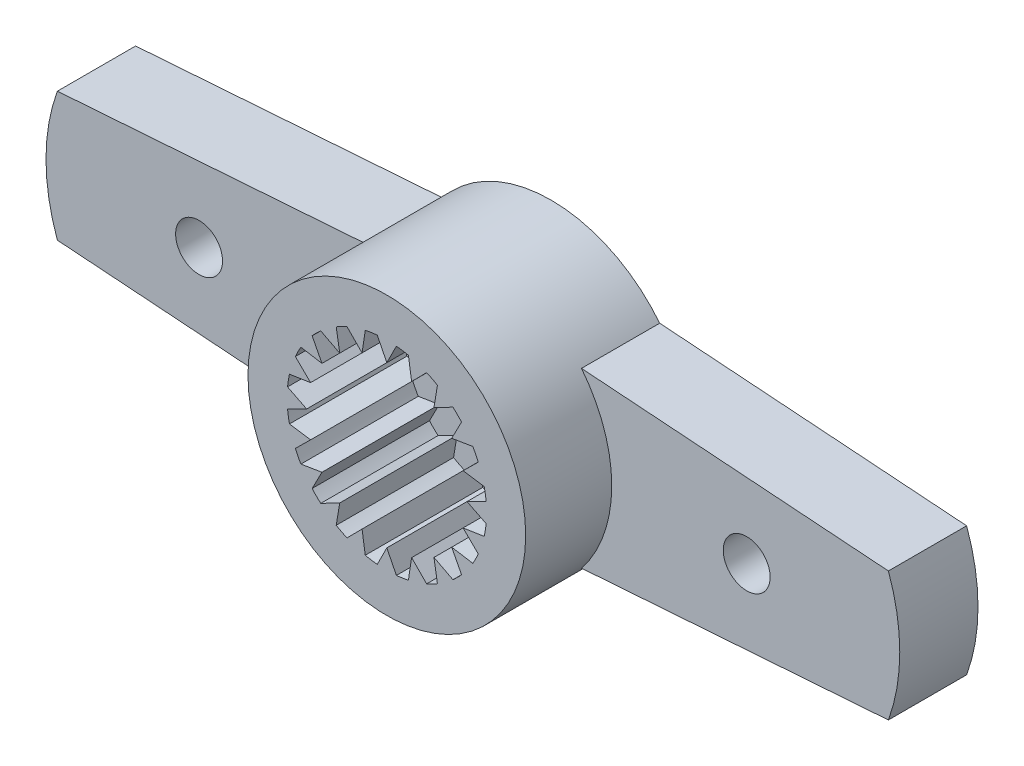
SolidWorks part; units mm, degrees
ref_plane "Front Plane" through (0, 0, 0) normal (0, 0, 1) x (1, 0, 0)
ref_plane "Top Plane" through (0, 0, 0) normal (0, 1, 0) x (1, 0, 0)
ref_plane "Right Plane" through (0, 0, 0) normal (1, 0, 0) x (0, 0, -1)
sketch "Sketch2" plane through (0, 0, 0) normal (0, 0, 1) x (1, 0, 0)
  circle A0 centre (0, 0) radius 3.55
  dimension "D1" = 7.1
sketch "Sketch3" plane through (0, 0, 0) normal (0, 0, 1) x (1, 0, 0)
  line L0 (-0.2447, 2.5382) -> (0, 2.05)
  line L1 (0, 2.05) -> (0.2447, 2.5382)
  line L2 (0.5516, 2.4896) -> (0.6335, 1.9497)
  line L3 (0.6335, 1.9497) -> (1.0171, 2.3384)
  line L4 (1.294, 2.1973) -> (1.205, 1.6585)
  line L5 (1.205, 1.6585) -> (1.6899, 1.9096)
  line L6 (1.9096, 1.6899) -> (1.6585, 1.205)
  line L7 (1.6585, 1.205) -> (2.1973, 1.294)
  line L8 (2.3384, 1.0171) -> (1.9497, 0.6335)
  line L9 (1.9497, 0.6335) -> (2.4896, 0.5516)
  line L10 (2.5382, 0.2447) -> (2.05, 0)
  line L11 (2.05, 0) -> (2.5382, -0.2447)
  line L12 (2.4896, -0.5516) -> (1.9497, -0.6335)
  line L13 (1.9497, -0.6335) -> (2.3384, -1.0171)
  line L14 (2.1973, -1.294) -> (1.6585, -1.205)
  line L15 (1.6585, -1.205) -> (1.9096, -1.6899)
  line L16 (1.6899, -1.9096) -> (1.205, -1.6585)
  line L17 (1.205, -1.6585) -> (1.294, -2.1973)
  line L18 (1.0171, -2.3384) -> (0.6335, -1.9497)
  line L19 (0.6335, -1.9497) -> (0.5516, -2.4896)
  line L20 (0.2447, -2.5382) -> (0, -2.05)
  line L21 (0, -2.05) -> (-0.2447, -2.5382)
  line L22 (-0.5516, -2.4896) -> (-0.6335, -1.9497)
  line L23 (-0.6335, -1.9497) -> (-1.0171, -2.3384)
  line L24 (-1.294, -2.1973) -> (-1.205, -1.6585)
  line L25 (-1.205, -1.6585) -> (-1.6899, -1.9096)
  line L26 (-1.9096, -1.6899) -> (-1.6585, -1.205)
  line L27 (-1.6585, -1.205) -> (-2.1973, -1.294)
  line L28 (-2.3384, -1.0171) -> (-1.9497, -0.6335)
  line L29 (-1.9497, -0.6335) -> (-2.4896, -0.5516)
  line L30 (-2.5382, -0.2447) -> (-2.05, 0)
  line L31 (-2.05, 0) -> (-2.5382, 0.2447)
  line L32 (-2.4896, 0.5516) -> (-1.9497, 0.6335)
  line L33 (-1.9497, 0.6335) -> (-2.3384, 1.0171)
  line L34 (-2.1973, 1.294) -> (-1.6585, 1.205)
  line L35 (-1.6585, 1.205) -> (-1.9096, 1.6899)
  line L36 (-1.6899, 1.9096) -> (-1.205, 1.6585)
  line L37 (-1.205, 1.6585) -> (-1.294, 2.1973)
  line L38 (-1.0171, 2.3384) -> (-0.6335, 1.9497)
  line L39 (-0.6335, 1.9497) -> (-0.5516, 2.4896)
  arc A0 (-0.2447, 2.5382) -> (0.2447, 2.5382) centre (0, 0) cw
  arc A2 (0.5516, 2.4896) -> (1.0171, 2.3384) centre (0, 0) cw
  arc A3 (1.294, 2.1973) -> (1.6899, 1.9096) centre (0, 0) cw
  arc A4 (1.9096, 1.6899) -> (2.1973, 1.294) centre (0, 0) cw
  arc A5 (2.3384, 1.0171) -> (2.4896, 0.5516) centre (0, 0) cw
  arc A6 (2.5382, 0.2447) -> (2.5382, -0.2447) centre (0, 0) cw
  arc A7 (2.4896, -0.5516) -> (2.3384, -1.0171) centre (0, 0) cw
  arc A8 (2.1973, -1.294) -> (1.9096, -1.6899) centre (0, 0) cw
  arc A9 (1.6899, -1.9096) -> (1.294, -2.1973) centre (0, 0) cw
  arc A10 (1.0171, -2.3384) -> (0.5516, -2.4896) centre (0, 0) cw
  arc A11 (0.2447, -2.5382) -> (-0.2447, -2.5382) centre (0, 0) cw
  arc A12 (-0.5516, -2.4896) -> (-1.0171, -2.3384) centre (0, 0) cw
  arc A13 (-1.294, -2.1973) -> (-1.6899, -1.9096) centre (0, 0) cw
  arc A14 (-1.9096, -1.6899) -> (-2.1973, -1.294) centre (0, 0) cw
  arc A15 (-2.3384, -1.0171) -> (-2.4896, -0.5516) centre (0, 0) cw
  arc A16 (-2.5382, -0.2447) -> (-2.5382, 0.2447) centre (0, 0) cw
  arc A17 (-2.4896, 0.5516) -> (-2.3384, 1.0171) centre (0, 0) cw
  arc A18 (-2.1973, 1.294) -> (-1.9096, 1.6899) centre (0, 0) cw
  arc A19 (-1.6899, 1.9096) -> (-1.294, 2.1973) centre (0, 0) cw
  arc A20 (-1.0171, 2.3384) -> (-0.5516, 2.4896) centre (0, 0) cw
  point P66 (0, 0)
  dimension "D1" = 20
ref_plane "Plane1" through (0, 0, -2.2) normal (0, 0, 1) x (1, 0, 0)
sketch "Sketch4" plane through (0, 0, -2.2) normal (0, 0, 1) x (1, 0, 0)
  line L0 (2.7764, 2.2123) -> (10.6226, 1.65)
  line L1 (2.7764, -2.2123) -> (10.6226, -1.65)
  arc A0 (10.6226, 1.65) -> (10.6226, -1.65) centre (6.0891, 0) cw
  arc A1 (2.7764, 2.2123) -> (2.7764, -2.2123) centre (0, 0) cw
extrude "Boss-Extrude1" add sketch "Sketch2" against normal blind 4.2 contours A0
extrude "Boss-Extrude2" add sketch "Sketch4" against normal up to surface (2 mm away) up to face at (3.55, 0, -4.2)
sketch "Sketch5" plane through (0, 0, 0) normal (0, 0, 1) x (1, 0, 0)
  circle A0 centre (0, 0) radius 2.55
extrude "Cut-Extrude1" cut sketch "Sketch5" against normal blind 3
extrude "Boss-Extrude3" add sketch "Sketch3" against normal up to surface (3 mm away) up to face at (2.55, 0, -3)
sketch "Sketch6" plane through (0, 0, -3) normal (0, 0, 1) x (1, 0, 0)
  circle A0 centre (0, 0) radius 1.4
  dimension "D1" = 2.8
extrude "Cut-Extrude2" cut sketch "Sketch6" against normal through all
sketch "Sketch7" plane through (0, 0, -2.2) normal (0, 0, 1) x (1, 0, 0)
  circle A0 centre (7, 0) radius 0.6
  dimension "D1" = 1.2
  dimension "D2" = 7
extrude "Cut-Extrude3" cut sketch "Sketch7" against normal through all
mirror "Mirror1" about plane through (0, 0, 0) normal (1, 0, 0) of "Boss-Extrude2"
mirror "Mirror2" about plane through (0, 0, 0) normal (1, 0, 0) of "Cut-Extrude3"
